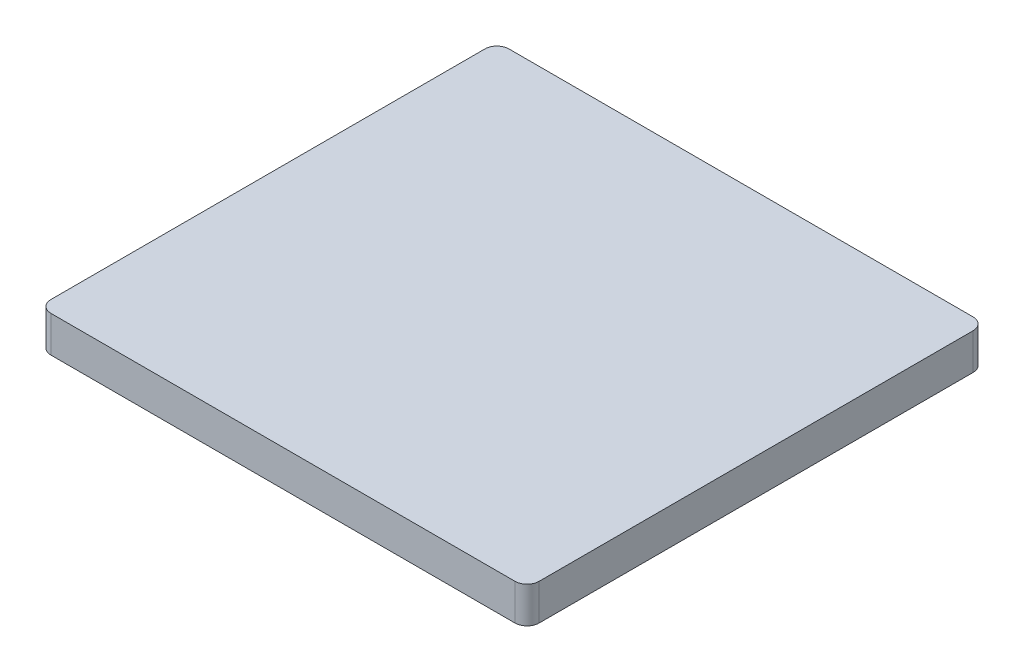
SolidWorks part; units mm, degrees
ref_plane "前视基准面" through (0, 0, 0) normal (0, 0, 1) x (1, 0, 0)
ref_plane "上视基准面" through (0, 0, 0) normal (0, 1, 0) x (1, 0, 0)
ref_plane "右视基准面" through (0, 0, 0) normal (1, 0, 0) x (0, 0, -1)
other "Configuration Table"
sketch "草图1" plane through (0, 0, 0) normal (0, 0, 1) x (1, 0, 0)
  line L0 (0, 0) -> (81, 0)
  line L1 (81, 0) -> (81, 6)
  line L2 (81, 6) -> (0, 6)
  line L3 (0, 6) -> (0, 0)
  dimension "width" = 81
  dimension "height" = 6
extrude "BlockExtrude" add sketch "草图1" along normal blind 76
fillet "Fillet" radius 2 4 edges at (0, 3, 0) (81, 3, 0) (0, 3, 76) (81, 3, 76)
